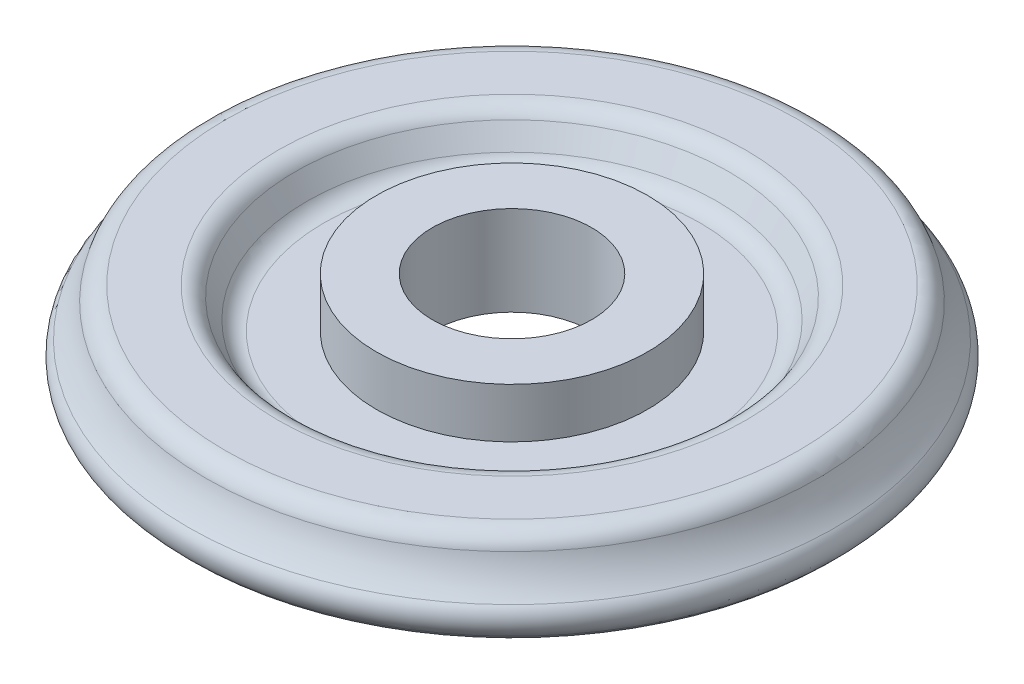
SolidWorks part; units mm, degrees
ref_plane "Front" through (0, 0, 0) normal (0, 0, 1) x (1, 0, 0)
ref_plane "Top" through (0, 0, 0) normal (0, 1, 0) x (1, 0, 0)
ref_plane "Right" through (0, 0, 0) normal (1, 0, 0) x (0, 0, -1)
sketch "Sketch1" plane through (0, 0, 0) normal (0, 0, 1) x (1, 0, 0)
  line L0 (0, 0) -> (25.4, 0)
  line L1 (25.4, 0) -> (26.9875, 1.5875)
  line L2 (24.13, 6.35) -> (17.7081, 6.35)
  line L3 (0, 3.175) -> (0, 0)
  line L4 (0, 4.7725) -> (0, 0) construction
  line L5 (0, 3.175) -> (15.875, 3.175)
  line L6 (15.875, 3.175) -> (17.7081, 6.35)
  arc A0 (24.13, 6.35) -> (26.9875, 1.5875) centre (30.4555, 6.9068) ccw
  dimension "D6" = 1.5875
  dimension "D9" = 6.35
  dimension "D1" = 25.4
  dimension "D2" = 45
  dimension "D3" = 24.13
  dimension "D4" = 6.35
  dimension "D5" = 3.175
  dimension "D7" = 15.875
  dimension "D8" = 60
revolve "Base-Revolve" add sketch "Sketch1" angle 360 about L4
fillet "Fillet1" radius 1.5875 4 edges at (0, 3.175, 15.875) (0, 6.35, 17.7081) (0, 6.35, 24.13) (0, 1.5875, 26.9875)
sketch "Sketch2" plane through (0, 3.175, 0) normal (0, 1, 0) x (-1, 0, 0)
  circle A0 centre (0, 0) radius 10.795
  dimension "D1" = 21.59
extrude "Round Boss" add sketch "Sketch2" along normal blind 3.9688
sketch "Sketch7" plane through (0, 7.1437, 0) normal (0, 1, 0) x (-1, 0, 0)
  line L1 (-12.465, 0) -> (-6.2325, -10.795)
  line L2 (-6.2325, -10.795) -> (6.2325, -10.795)
  line L3 (6.2325, -10.795) -> (12.465, 0)
  line L4 (12.465, 0) -> (6.2325, 10.795)
  line L5 (6.2325, 10.795) -> (-6.2325, 10.795)
  line L6 (-6.2325, 10.795) -> (-12.465, 0)
  circle A0 centre (0, 0) radius 10.795 construction
  circle A1 centre (0, 0) radius 10.795 construction
extrude "Pipe Thread1" [suppressed] add sketch "Sketch7" against normal up to surface (3.9688 mm away)
sketch "Sketch8" plane through (0, 7.1437, 0) normal (0, 1, 0) x (-1, 0, 0)
  circle A0 centre (0, 0) radius 9.525
  dimension "D1" = 19.05
extrude "Pipe Thread2" [suppressed] add sketch "Sketch8" along normal blind 12.7
chamfer "Pipe thread4" [suppressed] distance 0.7937 angle 45
sketch "Sketch9" plane through (0, 3.175, 0) normal (0, 1, 0) x (-1, 0, 0)
  line L0 (-9.525, 0) -> (9.525, 0) construction
  line L1 (-9.525, -9.525) -> (9.525, -9.525)
  line L2 (-9.525, -9.525) -> (-9.525, 9.525)
  line L3 (-9.525, 9.525) -> (9.525, 9.525)
  line L4 (9.525, -9.525) -> (9.525, 9.525)
  dimension "D1" = 19.05
extrude "Square1" [suppressed] add sketch "Sketch9" along normal blind 52.3875
sketch "Sketch10" [suppressed] plane through (9.525, 0, 0) normal (1, 0, 0) x (0, 0, -1)
  line L1 (-9.525, 55.5625) -> (9.525, 55.5625) construction
  line L2 (-9.525, 3.175) -> (9.525, 3.175) construction
  circle A0 centre (0, 46.0375) radius 3.3734
  circle A1 centre (0, 12.7) radius 3.3734
  dimension "D1" = 6.7469
  dimension "D2" = 9.525
  dimension "D3" = 9.525
extrude "Square2" [suppressed] cut sketch "Sketch10" against normal up to next
sketch "Sketch11" [suppressed] plane through (0, 0, 9.525) normal (0, 0, 1) x (1, 0, 0)
  line L0 (0, 55.5625) -> (0, 3.175) construction
  line L1 (-9.525, 55.5625) -> (9.525, 55.5625) construction
  line L2 (-9.525, 3.175) -> (9.525, 3.175) construction
  circle A0 centre (0, 30.1085) radius 3.3734
  dimension "D1" = 6.7469
extrude "Square3" [suppressed] cut sketch "Sketch11" against normal up to next
fillet "Square4" [suppressed] radius 1.5875
sketch "Sketch4" plane through (0, 0, 0) normal (0, 1, 0) x (-1, 0, 0)
  circle A0 centre (0, 0) radius 6.35
  dimension "D1" = 12.7
extrude "hole" cut sketch "Sketch4" along normal blind 6.35
sketch "Sketch12" plane through (0, 6.35, 0) normal (0, 1, 0) x (-1, 0, 0)
  circle A0 centre (0, 0) radius 6.35
  dimension "D1" = 12.7
extrude "Modular" cut sketch "Sketch12" along normal up to next
sketch "Sketch13" plane through (0, 7.1437, 0) normal (0, 1, 0) x (-1, 0, 0)
  circle A0 centre (0, 0) radius 7.9375
  dimension "D1" = 15.875
extrude "Grip Ring Stem1" [suppressed] add sketch "Sketch13" along normal blind 55.5625
sketch "Sketch14" [suppressed] plane through (0, 0, 0) normal (1, 0, 0) x (0, 0, -1)
  line L0 (7.9375, 7.1437) -> (7.9375, 62.7063) construction
  line L1 (7.9375, 62.7063) -> (-7.9375, 62.7063) construction
  line L2 (0, 65.1475) -> (0, 51.6264) construction
  line L3 (0, 7.1437) -> (0, 3.175) construction
  circle A0 centre (7.9375, 59.5313) radius 0.7937
  dimension "D1" = 1.5875
  dimension "D2" = 3.175
revolve "Grip Ring Stem2" [suppressed] add sketch "Sketch14" angle 360 about L2
sketch "Sketch15" plane through (0, 7.1437, 0) normal (0, 1, 0) x (-1, 0, 0)
  circle A0 centre (0, 0) radius 6.35
  dimension "D1" = 12.7
extrude "Threaded End1" [suppressed] add sketch "Sketch15" along normal blind 38.1
chamfer "Threaded End2" [suppressed] distance 0.7937 angle 45
sketch "Sketch5" plane through (0, 7.1437, 0) normal (0, 1, 0) x (-1, 0, 0)
  line L0 (-31.75, 0) -> (31.75, 0) construction
  line L1 (-25.4, -44.45) -> (25.4, -44.45)
  line L2 (-31.75, -38.1) -> (-31.75, 38.1)
  line L3 (-25.4, 44.45) -> (25.4, 44.45)
  line L4 (31.75, -38.1) -> (31.75, 38.1)
  arc A0 (-25.4, -44.45) -> (-31.75, -38.1) centre (-25.4, -38.1) cw
  arc A1 (-31.75, 38.1) -> (-25.4, 44.45) centre (-25.4, 38.1) cw
  arc A2 (25.4, 44.45) -> (31.75, 38.1) centre (25.4, 38.1) cw
  arc A3 (25.4, -44.45) -> (31.75, -38.1) centre (25.4, -38.1) ccw
  circle A4 centre (25.4, 38.1) radius 3.175
  circle A5 centre (25.4, -38.1) radius 3.175
  circle A6 centre (-25.4, 38.1) radius 3.175
  circle A7 centre (-25.4, -38.1) radius 3.175
  dimension "D1" = 6.35
  dimension "D4" = 6.35
  dimension "D2" = 88.9
  dimension "D3" = 63.5
extrude "Boltable Plate1" [suppressed] add sketch "Sketch5" along normal blind 3.175
sketch "Sketch6" [suppressed] plane through (0, 10.3187, 0) normal (0, 1, 0) x (-1, 0, 0)
  circle A0 centre (0, 0) radius 12.7
  dimension "D1" = 25.4
extrude "Boltable Plate2" [suppressed] cut sketch "Sketch6" against normal blind 1.5875 draft 15
fillet "Boltable Plate3" [suppressed] radius 0.7937
